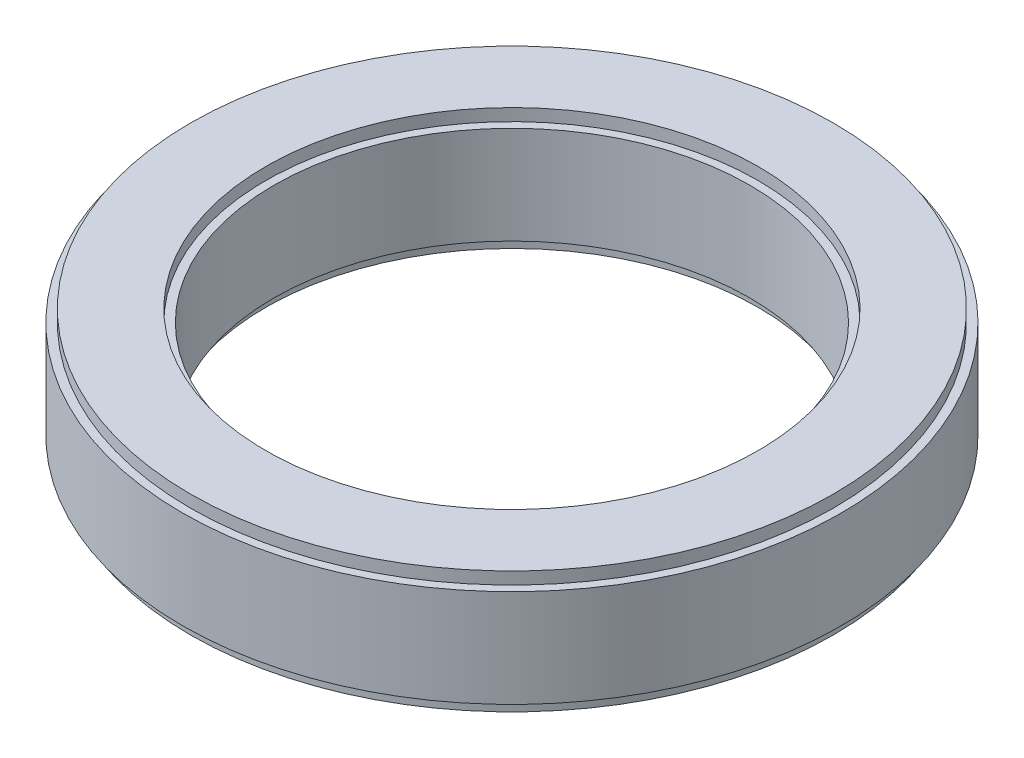
SolidWorks part; units mm, degrees
ref_plane "Front Plane" through (0, 0, 0) normal (0, 0, 1) x (1, 0, 0)
ref_plane "Top Plane" through (0, 0, 0) normal (0, 1, 0) x (1, 0, 0)
ref_plane "Right Plane" through (0, 0, 0) normal (1, 0, 0) x (0, 0, -1)
ref_axis "Axis1" through (0, 0, 0) along (0, 1, 0)
sketch "Sketch1" plane through (0, 0, 0) normal (0, 0, 1) x (1, 0, 0)
  line L0 (0, 0) -> (0, -27007.2749) construction
  line L3 (-40.5, 6) -> (-29.25, 6)
  line L4 (-40.5, 6) -> (-40.5, -6)
  line L5 (-40.5, -6) -> (-29.25, -6)
  line L6 (-29.25, 6) -> (-29.25, -6)
  point P7 (-29.25, 0)
  dimension "D1" = 12
  dimension "D2" = 81
  dimension "D3" = 58.5
revolve "Revolve1" add sketch "Sketch1" angle 360 about L0
sketch "Sketch2" plane through (0, 0, 0) normal (0, 0, 1) x (1, 0, 0)
  line L0 (-40.5, 6) -> (-29.25, 6) construction
  line L1 (-39.5, 7.5) -> (-30.25, 7.5)
  line L2 (-39.5, 7.5) -> (-39.5, -7.5)
  line L3 (-39.5, -7.5) -> (-30.25, -7.5)
  line L4 (-30.25, 7.5) -> (-30.25, -7.5)
  line L5 (-40.5, -6) -> (-29.25, -6) construction
  line L6 (-40.5, 6) -> (-40.5, -6) construction
  line L7 (-29.25, 6) -> (-29.25, -6) construction
  dimension "D1" = 1.5
  dimension "D2" = 1.5
  dimension "D3" = 1
  dimension "D4" = 1
revolve "Revolve2" add sketch "Sketch2" angle 360 about axis through (0, 0, 0) along (0, 1, 0)
